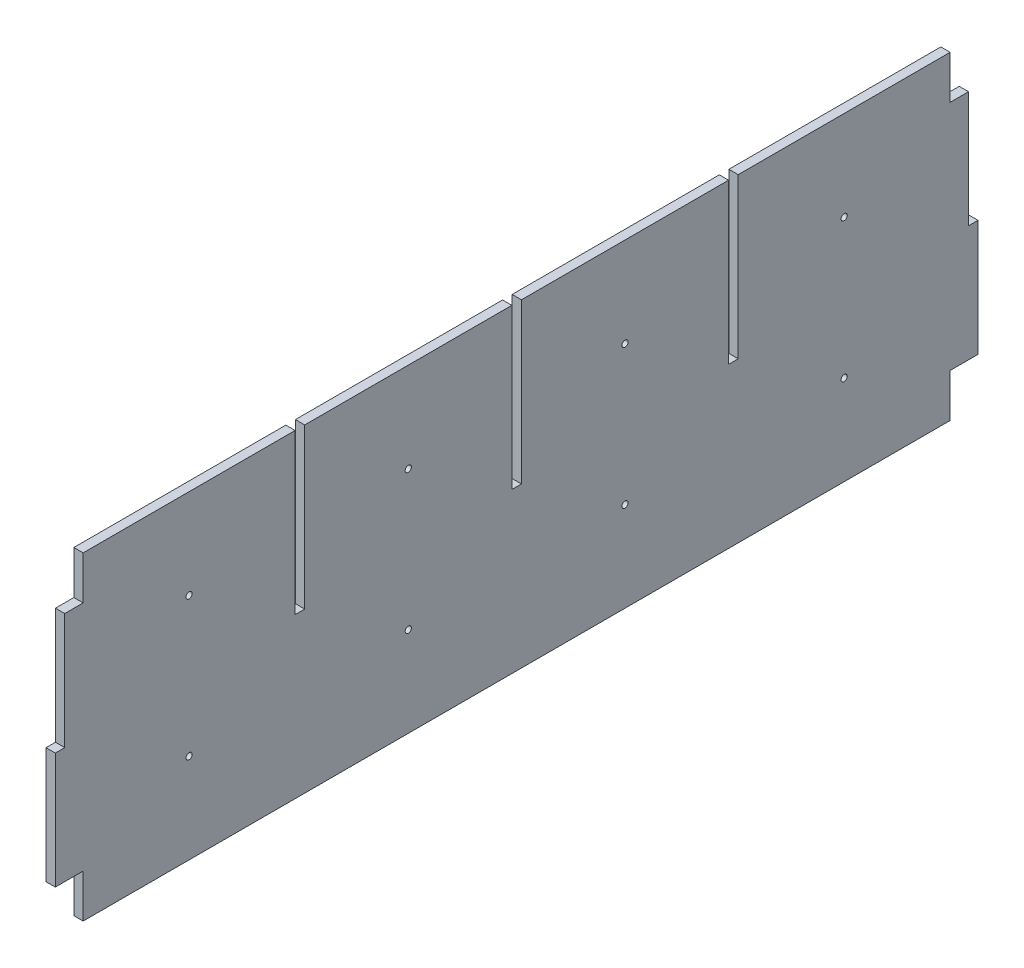
SolidWorks part; units mm, degrees
ref_plane "Front Plane" through (0, 0, 0) normal (0, 0, 1) x (1, 0, 0)
ref_plane "Top Plane" through (0, 0, 0) normal (0, 1, 0) x (1, 0, 0)
ref_plane "Right Plane" through (0, 0, 0) normal (1, 0, 0) x (0, 0, -1)
sketch "Sketch1" plane through (0, 0, 0) normal (1, 0, 0) x (0, 0, -1)
  line L0 (0, 0) -> (560, 0)
  line L1 (560, 0) -> (560, 10)
  line L2 (560, 10) -> (578, 10)
  line L3 (578, 10) -> (578, 85)
  line L4 (578, 85) -> (571.9, 85)
  line L5 (571.9, 85) -> (571.9, 160)
  line L6 (571.9, 160) -> (560, 160)
  line L7 (560, 160) -> (560, 170)
  line L8 (560, 170) -> (0, 170)
  line L9 (0, 170) -> (0, 160)
  line L10 (0, 160) -> (-11.9, 160)
  line L11 (-11.9, 160) -> (-11.9, 85)
  line L12 (-11.9, 85) -> (-18, 85)
  line L13 (-18, 85) -> (-18, 10)
  line L14 (0, 10) -> (0, 0)
  line L15 (-18, 10) -> (0, 10)
  dimension "D1" = 560
  dimension "D2" = 10
  dimension "D3" = 18
  dimension "D4" = 75
  dimension "D5" = 75
  dimension "D6" = 6.1
  dimension "D7" = 11.9
  dimension "D8" = 10
  dimension "D9" = 11.9
  dimension "D10" = 6.1
extrude "Boss-Extrude1" add sketch "Sketch1" along normal blind 6
sketch "Sketch2" plane through (6, 0, 0) normal (1, 0, 0) x (0, 0, -1)
  line L0 (560, 170) -> (0, 170) construction
  line L1 (136.9, 170) -> (143.1, 170)
  line L2 (136.9, 170) -> (136.9, 85)
  line L3 (136.9, 85) -> (143.1, 85)
  line L4 (143.1, 170) -> (143.1, 85)
  line L6 (276.9, 170) -> (283.1, 170)
  line L7 (276.9, 170) -> (276.9, 85)
  line L8 (276.9, 85) -> (283.1, 85)
  line L9 (283.1, 170) -> (283.1, 85)
  line L10 (416.9, 170) -> (423.1, 170)
  line L11 (416.9, 170) -> (416.9, 85)
  line L12 (416.9, 85) -> (423.1, 85)
  line L13 (423.1, 170) -> (423.1, 85)
  point P6 (140, 170)
  point P13 (280, 170)
  point P18 (420, 170)
  dimension "D1" = 0
  dimension "D2" = 140
  dimension "D3" = 6.2
  dimension "D4" = 140
  dimension "D5" = 6.2
  dimension "D6" = 140
  dimension "D7" = 6.2
extrude "Cut-Extrude1" cut sketch "Sketch2" against normal blind 6
sketch "Sketch3" plane through (6, 0, 0) normal (1, 0, 0) x (0, 0, -1)
  line L0 (136.9, 170) -> (0, 170) construction
  circle A0 centre (68.45, 130) radius 2
  circle A1 centre (68.45, 40) radius 2
  circle A2 centre (210, 130) radius 2
  circle A3 centre (210, 40) radius 2
  circle A4 centre (350, 130) radius 2
  circle A5 centre (350, 40) radius 2
  circle A6 centre (491.55, 130) radius 2
  circle A7 centre (491.55, 40) radius 2
  point P4 (68.45, 170)
  dimension "D2" = 4
  dimension "D5" = 4
  dimension "D6" = 4
  dimension "D7" = 4
  dimension "D8" = 4
  dimension "D9" = 4
  dimension "D10" = 4
  dimension "D11" = 4
  dimension "D1" = 0
  dimension "D3" = 30
  dimension "D4" = 30
extrude "Cut-Extrude2" cut sketch "Sketch3" against normal blind 6
sketch "Sketch4" plane through (0, 170, 0) normal (0, 1, 0) x (1, 0, 0)
  line L1 (6, 0) -> (0, 0)
  line L2 (6, 0) -> (6, 136.9)
  line L3 (6, 136.9) -> (0, 136.9)
  line L4 (0, 0) -> (0, 136.9)
  line L5 (6, 143.1) -> (0, 143.1)
  line L6 (6, 143.1) -> (6, 276.9)
  line L7 (6, 276.9) -> (0, 276.9)
  line L8 (0, 143.1) -> (0, 276.9)
  line L9 (6, 283.1) -> (0, 283.1)
  line L10 (6, 283.1) -> (6, 416.9)
  line L11 (6, 416.9) -> (0, 416.9)
  line L12 (0, 283.1) -> (0, 416.9)
  line L13 (6, 422.5352) -> (0, 422.5352)
  line L14 (6, 422.5352) -> (6, 560)
  line L15 (6, 560) -> (0, 560)
  line L16 (0, 422.5352) -> (0, 560)
extrude "Boss-Extrude2" add sketch "Sketch4" along normal blind 28
sketch "Sketch5" plane through (0, 0, 0) normal (0, -1, 0) x (1, 0, 0)
  line L1 (6, -560) -> (0, -560)
  line L2 (6, -560) -> (6, 0)
  line L3 (6, 0) -> (0, 0)
  line L4 (0, -560) -> (0, 0)
extrude "Boss-Extrude3" add sketch "Sketch5" along normal blind 28
sketch "Sketch6" plane through (0, 170, 0) normal (0, -1, 0) x (1, 0, 0)
  line L1 (0, -423.1) -> (6, -423.1)
  line L2 (0, -423.1) -> (0, -422.5352)
  line L3 (0, -422.5352) -> (6, -422.5352)
  line L4 (6, -423.1) -> (6, -422.5352)
extrude "Cut-Extrude3" cut sketch "Sketch6" against normal blind 28
sketch "Sketch7" plane through (0, 0, -560) normal (0, 0, -1) x (-1, 0, 0)
  line L0 (0, 160) -> (0, 198) construction
  line L1 (-6, 198) -> (0, 198)
  line L2 (-6, 198) -> (-6, 188)
  line L3 (-6, 188) -> (0, 188)
  line L4 (0, 198) -> (0, 188)
  line L5 (-6, -28) -> (-6, 10) construction
  line L6 (0, -28) -> (-6, -28)
  line L7 (0, -28) -> (0, -18)
  line L8 (0, -18) -> (-6, -18)
  line L9 (-6, -28) -> (-6, -18)
  dimension "D1" = 10
  dimension "D2" = 10
extrude "Cut-Extrude4" cut sketch "Sketch7" against normal blind 1000
